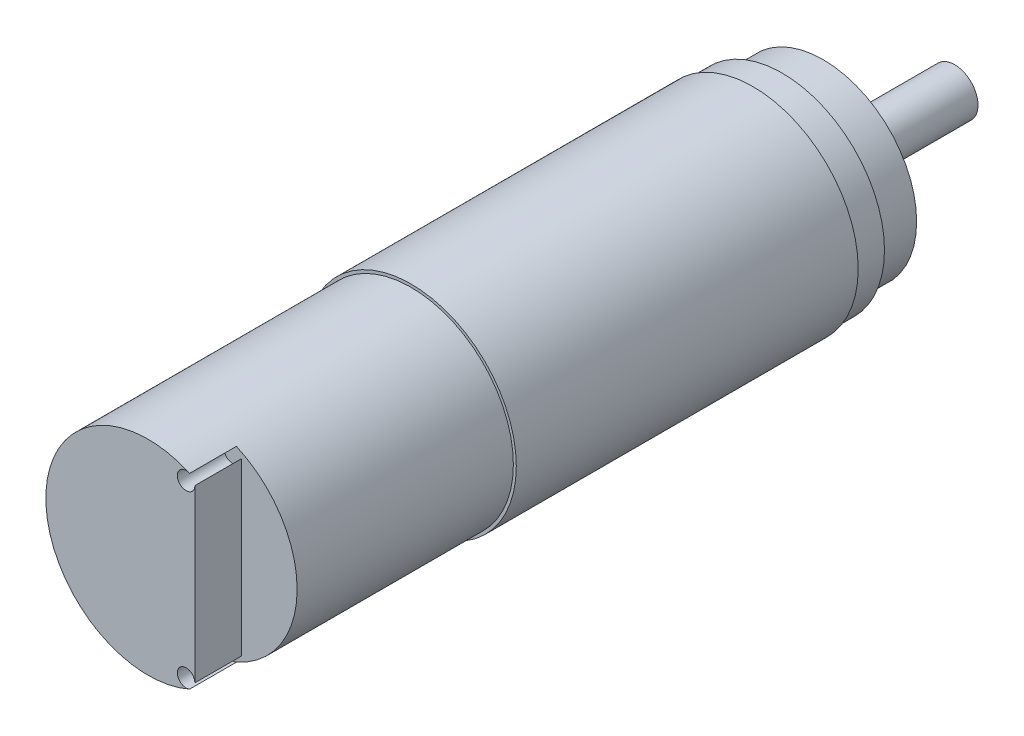
SolidWorks part; units mm, degrees
ref_plane "Front Plane" through (0, 0, 0) normal (0, 0, 1) x (1, 0, 0)
ref_plane "Top Plane" through (0, 0, 0) normal (0, 1, 0) x (1, 0, 0)
ref_plane "Right Plane" through (0, 0, 0) normal (1, 0, 0) x (0, 0, -1)
sketch "Sketch1" plane through (0, 0, 0) normal (0, 0, 1) x (1, 0, 0)
  line L0 (4.1859, 0) -> (0, 0) construction
  line L1 (0, 0) -> (9.8995, -9.8995) construction
  circle A0 centre (0, 0) radius 14 construction
  circle A1 centre (0, 0) radius 11.25
  circle A2 centre (0, 0) radius 16
  circle A3 centre (9.8995, -9.8995) radius 1.75
  circle A4 centre (-9.8995, -9.8995) radius 1.75
  circle A5 centre (-9.8995, 9.8995) radius 1.75
  circle A6 centre (9.8995, 9.8995) radius 1.75
  point P17 (0, 0)
  dimension "D1" = 28
  dimension "D2" = 32
  dimension "D4" = 3.5
  dimension "D5" = 22.5
  dimension "D3" = 45
  dimension "D6" = 4
extrude "Boss-Extrude1" add sketch "Sketch1" along normal blind 7 contours A1 | A2 A6 A5 A4 A3 A1
sketch "Sketch2" plane through (0, 0, 7) normal (0, 0, 1) x (1, 0, 0)
  circle A0 centre (0, 0) radius 17.5
  dimension "D1" = 35
extrude "Boss-Extrude2" add sketch "Sketch2" along normal blind 108.5
sketch "Sketch3" plane through (0, 0, 0) normal (0, 0, -1) x (-1, 0, 0)
  circle A0 centre (0, 0) radius 4
  dimension "D1" = 8
extrude "Boss-Extrude3" add sketch "Sketch3" along normal blind 22.5
sketch "Sketch4" plane through (0, 0, 115.5) normal (0, 0, 1) x (1, 0, 0)
  circle A0 centre (0, 0) radius 18
  circle A1 centre (0, 0) radius 17.5 construction
  circle A2 centre (0, 0) radius 17.5
  dimension "D1" = 0.5
extrude "Boss-Extrude4" add sketch "Sketch4" against normal offset from surface (58.5 mm away) 5 from offset 45 up to face at (16, 0, 7) offset against normal yes
sketch "Sketch5" plane through (0, 0, 115.5) normal (0, 0, 1) x (1, 0, 0)
  line L0 (8, 15.5644) -> (8, -15.5644)
  line L1 (0, 0) -> (8, 0) construction
  circle A0 centre (0, 0) radius 17.5 construction
  circle A3 centre (0, 0) radius 17.5
  arc A4 (8, -15.5644) -> (8, 15.5644) centre (0, 0) ccw
  dimension "D1" = 8
  dimension "D2" = 0
extrude "Cut-Extrude1" cut sketch "Sketch5" against normal blind 8
sketch "Sketch6" plane through (0, 0, 115.5) normal (0, 0, 1) x (1, 0, 0)
  line L0 (8, 15.5644) -> (8, -15.5644) construction
  line L1 (0, 0) -> (9.5894, 0) construction
  line L2 (8, 14.6202) -> (8, 15.5644)
  line L3 (8, -15.5644) -> (8, 15.5644)
  line L4 (8, -15.5644) -> (8, -14.6202)
  arc A0 (7.1094, 15.9908) -> (8, 14.6202) centre (6.5, 14.6202) ccw
  arc A1 (8, 15.5644) -> (8, -15.5644) centre (0, 0) ccw construction
  arc A2 (7.1094, -15.9908) -> (8, -14.6202) centre (6.5, -14.6202) cw
  arc A3 (7.1094, -15.9908) -> (8, -15.5644) centre (0, 0) ccw
  arc A4 (8, 15.5644) -> (8, -15.5644) centre (0, 0) ccw
  arc A5 (8, 15.5644) -> (7.1094, 15.9908) centre (0, 0) ccw
  dimension "D1" = 3
  dimension "D2" = 0
extrude "Cut-Extrude3" cut sketch "Sketch6" against normal up to surface (8 mm away) up to face at (12.75, 0, 107.5)
